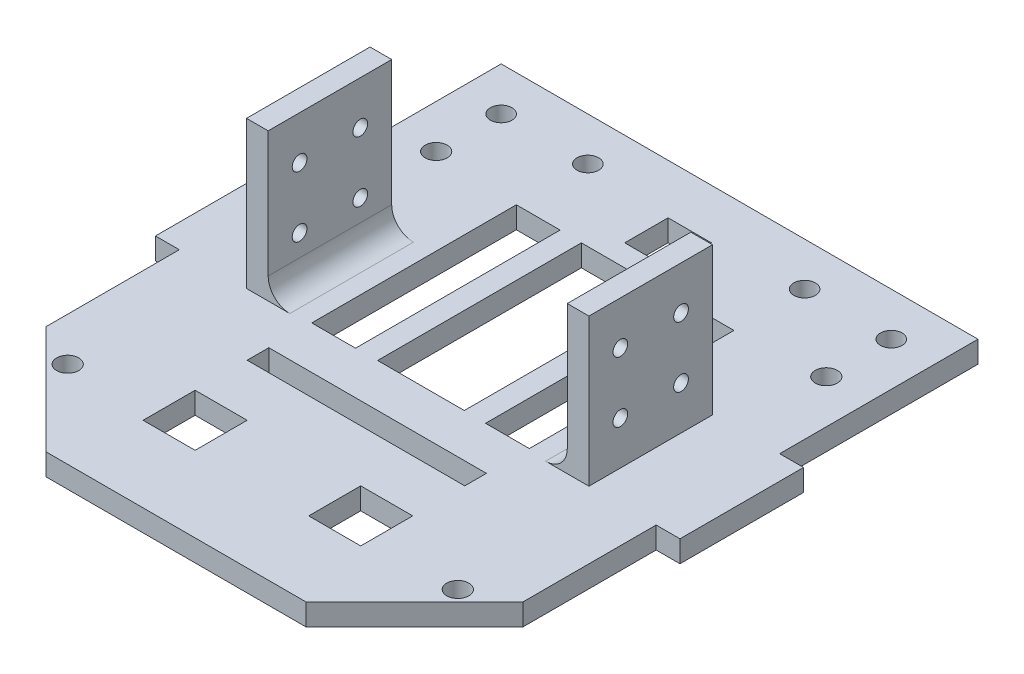
SolidWorks part; units mm, degrees
ref_plane "Front Plane" through (0, 0, 0) normal (0, 0, 1) x (1, 0, 0)
ref_plane "Top Plane" through (0, 0, 0) normal (0, 1, 0) x (1, 0, 0)
ref_plane "Right Plane" through (0, 0, 0) normal (1, 0, 0) x (0, 0, -1)
sketch "Sketch1" plane through (0, 0, 0) normal (0, 1, 0) x (1, 0, 0)
  line L0 (0, 0) -> (10, 0) construction
  line L1 (-55, 80) -> (55, 80)
  line L2 (-55, 80) -> (-55, -80)
  line L3 (-55, -80) -> (55, -80)
  line L4 (55, 80) -> (55, -80)
  line L5 (-55, 80) -> (55, -80) construction
  line L6 (-55, -80) -> (55, 80) construction
  line L7 (-10, 23.5) -> (10, 23.5)
  line L8 (-10, 23.5) -> (-10, -23.5)
  line L9 (-10, -23.5) -> (10, -23.5)
  line L10 (10, 23.5) -> (10, -23.5)
  line L11 (-10, 23.5) -> (10, -23.5) construction
  line L12 (-10, -23.5) -> (10, 23.5) construction
  line L14 (0, 0) -> (0, 35.7746) construction
  line L17 (-55, -80) -> (-20, -80)
  line L18 (-55, -80) -> (-55, -21.75)
  line L22 (-55, 80) -> (55, 80)
  line L23 (-55, 80) -> (-55, 50)
  line L24 (-55, 50) -> (55, 50)
  line L25 (55, 80) -> (55, 50)
  line L31 (-55, 21.75) -> (-55, -21.75)
  line L35 (55, 21.75) -> (55, -21.75)
  line L36 (-20, 80) -> (20, 80)
  line L40 (-20, -80) -> (20, -80)
  line L46 (2.5, -80) -> (42.5, -80)
  point P0 (0, 0)
  point P6 (0, 0)
  point P13 (0, 0)
  dimension "D9" = 30
  dimension "D1" = 160
  dimension "D2" = 110
  dimension "D3" = 47
  dimension "D4" = 20
extrude "Boss-Extrude3" add sketch "Sketch1" along normal blind 5
sketch "Sketch2" plane through (0, 0, 0) normal (0, -1, 0) x (1, 0, 0)
  line L0 (0, 0) -> (0, -18.1723) construction
  line L1 (-10, 23.5) -> (-15, 23.5)
  line L2 (-10, 23.5) -> (-10, -23.5)
  line L3 (-10, -23.5) -> (-15, -23.5)
  line L4 (-15, 23.5) -> (-15, -23.5)
  line L5 (10, 23.5) -> (15, 23.5)
  line L6 (10, 23.5) -> (10, -23.5)
  line L7 (10, -23.5) -> (15, -23.5)
  line L8 (15, 23.5) -> (15, -23.5)
  line L9 (-15, 23.5) -> (-25.1, 23.5)
  line L10 (-15, 23.5) -> (-15, -23.5)
  line L11 (-15, -23.5) -> (-25.1, -23.5)
  line L12 (-25.1, 23.5) -> (-25.1, -23.5)
  line L13 (15, 23.5) -> (25.1, 23.5)
  line L14 (15, 23.5) -> (15, -23.5)
  line L15 (15, -23.5) -> (25.1, -23.5)
  line L16 (25.1, 23.5) -> (25.1, -23.5)
  line L25 (-25.1, 23.6) -> (-15, 23.6)
  line L26 (-25.1, 23.6) -> (-25.1, -23.6)
  line L27 (-25.1, -23.6) -> (-15, -23.6)
  line L28 (-15, 23.6) -> (-15, -23.6)
  line L29 (15, 23.6) -> (25.1, 23.6)
  line L30 (15, 23.6) -> (15, -23.6)
  line L31 (15, -23.6) -> (25.1, -23.6)
  line L32 (25.1, 23.6) -> (25.1, -23.6)
  line L49 (-10, 23.5) -> (10, 23.5) construction
  line L50 (-25.1, 38.5) -> (25.1, 38.5)
  line L51 (-25.1, 38.5) -> (-25.1, 33.5)
  line L52 (-25.1, 33.5) -> (25.1, 33.5)
  line L53 (25.1, 38.5) -> (25.1, 33.5)
  dimension "D1" = 5
  dimension "D2" = 5
  dimension "D3" = 10.1
  dimension "D4" = 10.1
  dimension "D5" = 47
  dimension "D6" = 10
  dimension "D7" = 50.2
  dimension "D8" = 5
  dimension "D10" = 0.1
  dimension "D11" = 0.1
  dimension "D12" = 0.1
  dimension "D13" = 0.1
extrude "Cut-Extrude1" cut sketch "Sketch2" against normal blind 15
sketch "Sketch3" plane through (0, 5, 0) normal (0, 1, 0) x (1, 0, 0)
  line L0 (-55, 50) -> (55, 50) construction
  line L1 (-55, 50) -> (-55, -80) construction
  line L2 (-55, -80) -> (55, -80) construction
  line L3 (0, 0) -> (0, -64.7201) construction
  circle A0 centre (-45, 25) radius 2.55
  circle A1 centre (-45, -60) radius 2.55
  circle A2 centre (45, -60) radius 2.55
  circle A3 centre (45, 25) radius 2.55
  dimension "D1" = 5.1
  dimension "D2" = 5.1
  dimension "D3" = 25
  dimension "D4" = 10
  dimension "D5" = 20
  dimension "D6" = 10
extrude "Cut-Extrude3" cut sketch "Sketch3" against normal blind 10
sketch "Sketch4" plane through (0, 5, 0) normal (0, 1, 0) x (1, 0, 0)
  line L1 (-34.5, 4.25) -> (-39.5, 4.25)
  line L2 (-34.5, 4.25) -> (-34.5, -24.25)
  line L3 (-34.5, -24.25) -> (-39.5, -24.25)
  line L4 (-39.5, 4.25) -> (-39.5, -24.25)
  line L5 (-55, -80) -> (55, -80) construction
  line L6 (-55, 50) -> (55, 50) construction
  line L7 (0, 0) -> (0, -22.3797) construction
  line L8 (39.5, 4.25) -> (39.5, -24.25)
  line L9 (34.5, -24.25) -> (39.5, -24.25)
  line L10 (34.5, 4.25) -> (34.5, -24.25)
  line L11 (34.5, 4.25) -> (39.5, 4.25)
  line L12 (-10, 23.5) -> (-10, -23.5) construction
  dimension "D1" = 5
  dimension "D2" = 29.5
  dimension "D3" = 55.75
  dimension "D4" = 45.75
extrude "Boss-Extrude4" add sketch "Sketch4" along normal blind 34
sketch "Sketch5" plane through (-39.5, 0, 0) normal (-1, 0, 0) x (0, 0, 1)
  line L0 (10, 39) -> (10, 5) construction
  line L1 (-4.25, 39) -> (24.25, 39) construction
  line L2 (-4.25, 5) -> (24.25, 5) construction
  line L4 (3, 29) -> (17, 29)
  line L5 (3, 29) -> (3, 15)
  line L6 (3, 15) -> (17, 15)
  line L7 (17, 29) -> (17, 15)
  line L8 (3, 29) -> (17, 15) construction
  line L9 (3, 15) -> (17, 29) construction
  circle A0 centre (17, 29) radius 1.7
  circle A1 centre (3, 29) radius 1.7
  circle A2 centre (3, 15) radius 1.7
  circle A3 centre (17, 15) radius 1.7
  point P6 (10, 22)
  dimension "D3" = 3.4
  dimension "D1" = 14
  dimension "D2" = 14
  dimension "D4" = 2
  dimension "D5" = 2
extrude "Cut-Extrude4" cut sketch "Sketch5" against normal through all contours L5 A2 L6 | L4 A1 L5 | L7 A0 L4 | L6 A3 L7 | L7 A3 L6 | L4 A0 L7 | L6 A2 L5 | L5 A1 L4
fillet "Fillet1" radius 5 2 edges at (34.5, 5, 10) (-34.5, 5, 10)
sketch "Sketch6" plane through (0, 5, 0) normal (0, 1, 0) x (1, 0, 0)
  line L0 (-55, 50) -> (-55, -80) construction
  line L1 (-55, -24.25) -> (-60.5, -24.25)
  line L2 (-55, -24.25) -> (-55, 4.25)
  line L3 (-55, 4.25) -> (-60.5, 4.25)
  line L4 (-60.5, -24.25) -> (-60.5, 4.25)
  line L7 (-10, 23.5) -> (10, 23.5) construction
  line L10 (-10, -23.5) -> (10, -23.5) construction
  line L14 (0, 0) -> (0, -21.1421) construction
  line L15 (60.5, -24.25) -> (60.5, 4.25)
  line L16 (55, 4.25) -> (60.5, 4.25)
  line L17 (55, -24.25) -> (55, 4.25)
  line L18 (55, -24.25) -> (60.5, -24.25)
  dimension "D1" = 19.25
  dimension "D2" = 0.75
  dimension "D3" = 5.5
extrude "Boss-Extrude5" add sketch "Sketch6" against normal blind 5
sketch "Sketch9" plane through (0, 5, 0) normal (0, 1, 0) x (1, 0, 0)
  line L0 (-55, 50) -> (55, 50) construction
  line L1 (-55, 50) -> (-55, 4.25) construction
  line L2 (0, 0) -> (0, 16.6281) construction
  circle A0 centre (-45, 40) radius 2.5
  circle A1 centre (45, 40) radius 2.5
  circle A2 centre (-25, 40) radius 2.5
  circle A3 centre (25, 40) radius 2.5
  dimension "D1" = 5
  dimension "D2" = 10
  dimension "D3" = 10
  dimension "D4" = 2
  dimension "D5" = 2
extrude "Cut-Extrude7" cut sketch "Sketch9" against normal blind 180
chamfer "Chamfer1" distance 25 angle 45 2 edges at (55, 2.5, 80) (-55, 2.5, 80)
sketch "Sketch10" plane through (0, 5, 0) normal (0, 1, 0) x (1, 0, 0)
  line L0 (-25.1, -33.5) -> (-25.1, -38.5) construction
  line L1 (-5, 38.5) -> (5, 38.5)
  line L2 (-5, 38.5) -> (-5, 28.5)
  line L3 (-5, 28.5) -> (5, 28.5)
  line L4 (5, 38.5) -> (5, 28.5)
  line L5 (-25.1, -50.5) -> (-13.1, -50.5)
  line L6 (-25.1, -50.5) -> (-25.1, -62.5)
  line L7 (-25.1, -62.5) -> (-13.1, -62.5)
  line L8 (-13.1, -50.5) -> (-13.1, -62.5)
  line L9 (13.1, -50.5) -> (25.1, -50.5)
  line L10 (13.1, -50.5) -> (13.1, -62.5)
  line L11 (13.1, -62.5) -> (25.1, -62.5)
  line L12 (25.1, -50.5) -> (25.1, -62.5)
  line L13 (25.1, -33.5) -> (25.1, -38.5) construction
  line L15 (25.1, -38.5) -> (-25.1, -38.5) construction
  line L16 (-10, 23.5) -> (-10, -23.5) construction
  line L17 (10, 23.5) -> (10, -23.5) construction
  line L18 (-10, 23.5) -> (10, 23.5) construction
  dimension "D1" = 0
  dimension "D2" = 0
  dimension "D3" = 12
  dimension "D4" = 12
  dimension "D5" = 12
  dimension "D6" = 12
  dimension "D7" = 12
  dimension "D8" = 12
  dimension "D9" = 5
  dimension "D10" = 5
  dimension "D11" = 5
  dimension "D12" = 10
extrude "Cut-Extrude8" cut sketch "Sketch10" against normal through all
